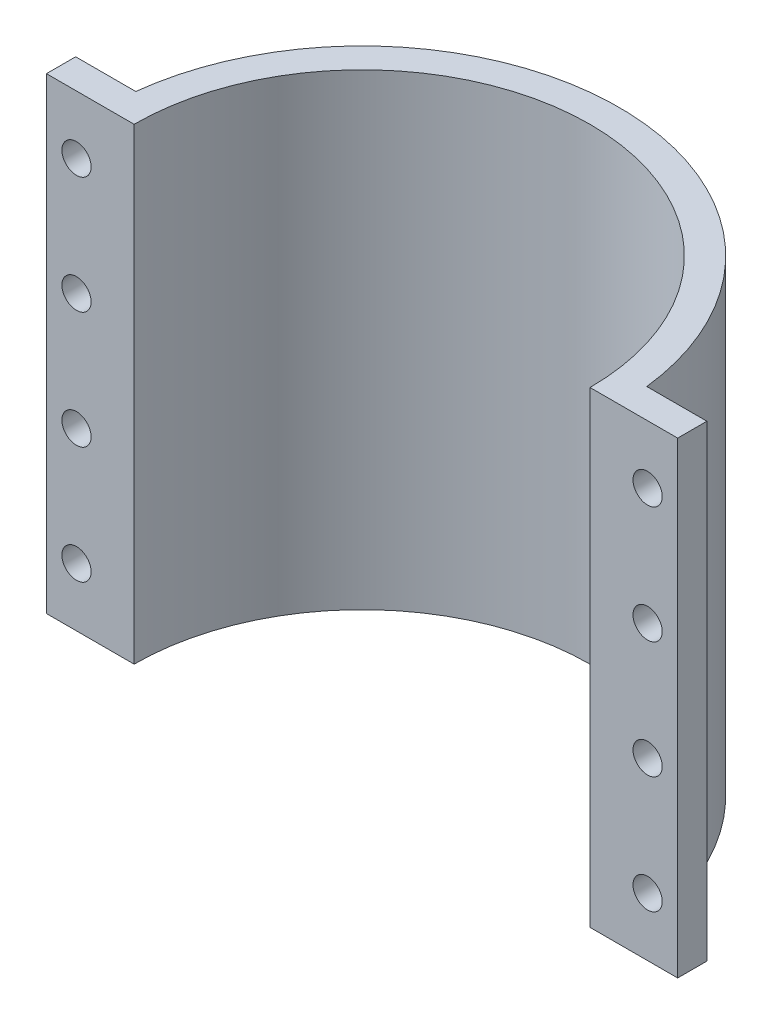
SolidWorks part; units mm, degrees
ref_plane "Front Plane" through (0, 0, 0) normal (0, 0, 1) x (1, 0, 0)
ref_plane "Top Plane" through (0, 0, 0) normal (0, 1, 0) x (1, 0, 0)
ref_plane "Right Plane" through (0, 0, 0) normal (1, 0, 0) x (0, 0, -1)
sketch "Sketch1" plane through (0, 0, 0) normal (0, 1, 0) x (1, 0, 0)
  line L0 (0, 87.8593) -> (0, -74.8135) construction
  line L1 (-127.5291, 0) -> (112.8859, 0) construction
  line L2 (55.518, 6.35) -> (68.58, 6.35)
  line L3 (-49.53, 0) -> (-68.58, 0)
  line L5 (-55.518, 6.35) -> (-68.58, 6.35)
  line L6 (-68.58, 0) -> (-68.58, 6.35)
  line L7 (49.53, 0) -> (68.58, 0)
  line L8 (68.58, 0) -> (68.58, 6.35)
  arc A0 (55.518, 6.35) -> (-55.518, 6.35) centre (0, 0) ccw
  arc A1 (49.53, 0) -> (-49.53, 0) centre (0, 0) ccw
  dimension "D1" = 99.06
  dimension "D2" = 111.76
  dimension "D3" = 6.35
  dimension "D4" = 19.05
extrude "Boss-Extrude1" add sketch "Sketch1" along normal blind 101.6
sketch "Sketch2" plane through (0, 0, -6.35) normal (0, 0, -1) x (-1, 0, 0)
  line L0 (62.049, 108.7641) -> (62.049, -28.1573) construction
  line L1 (55.518, 101.6) -> (55.518, 0) construction
  line L2 (68.58, 101.6) -> (68.58, 0) construction
  line L3 (55.518, 101.6) -> (68.58, 101.6) construction
  line L4 (0, 111.274) -> (0, -32.59) construction
  circle A0 centre (62.049, 88.9) radius 3.175
  circle A4 centre (62.049, 63.5) radius 3.175
  circle A5 centre (62.049, 38.1) radius 3.175
  circle A6 centre (62.049, 12.7) radius 3.175
  circle A7 centre (-62.049, 12.7) radius 3.175
  circle A8 centre (-62.049, 38.1) radius 3.175
  circle A9 centre (-62.049, 63.5) radius 3.175
  circle A10 centre (-62.049, 88.9) radius 3.175
  dimension "D1" = 6.35
  dimension "D3" = 4
  dimension "D2" = 12.7
extrude "Cut-Extrude1" cut sketch "Sketch2" against normal through all
